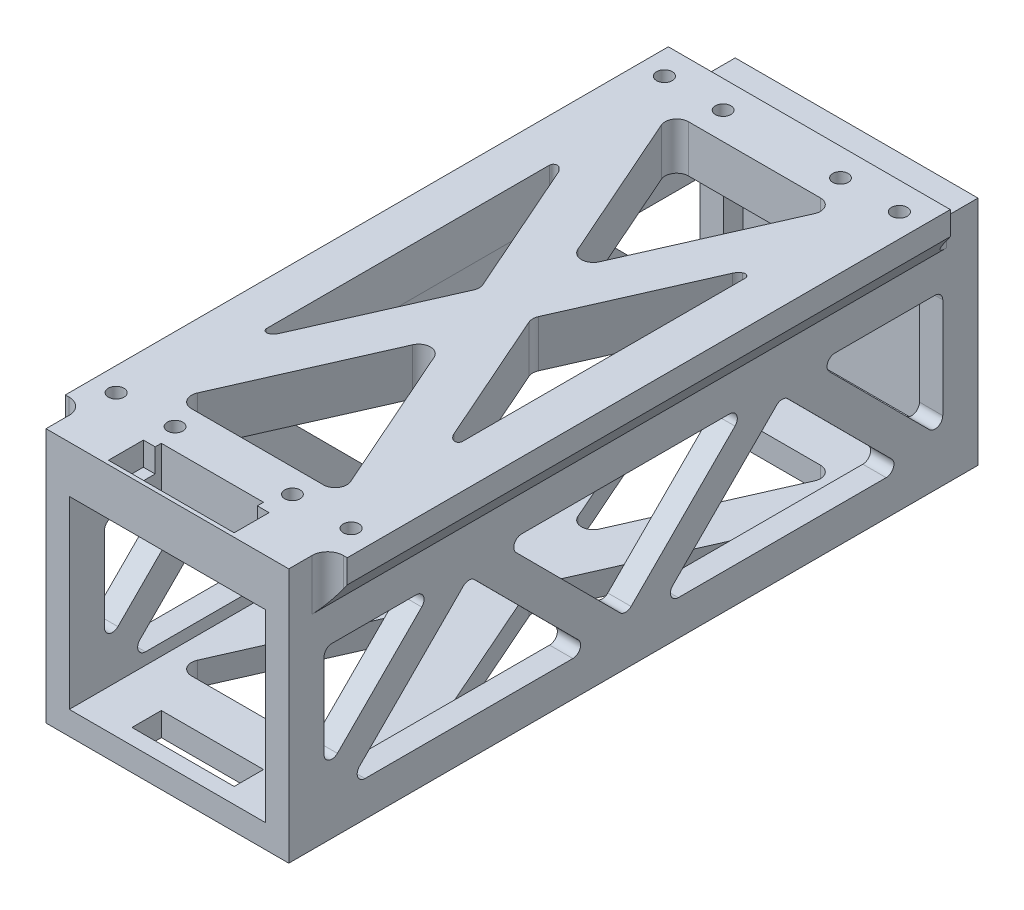
SolidWorks part; units mm, degrees
material "PBT General Purpose"
ref_plane "Front Plane" through (0, 0, 0) normal (0, 0, 1) x (1, 0, 0)
ref_plane "Top Plane" through (0, 0, 0) normal (0, 1, 0) x (1, 0, 0)
ref_plane "Right Plane" through (0, 0, 0) normal (1, 0, 0) x (0, 0, -1)
sketch "Sketch1" plane through (0, 0, 0) normal (0, 1, 0) x (1, 0, 0)
  line L1 (-31, -86) -> (31, -86)
  line L2 (-31, -86) -> (-31, 86)
  line L3 (-31, 86) -> (31, 86)
  line L4 (31, -86) -> (31, 86)
  line L5 (-31, -86) -> (31, 86) construction
  line L6 (-31, 86) -> (31, -86) construction
  point P0 (0, 0)
  dimension "D1" = 62
  dimension "D2" = 172
extrude "Boss-Extrude1" add sketch "Sketch1" along normal blind 6
sketch "Sketch2" plane through (0, 6, 0) normal (0, 1, 0) x (1, 0, 0)
  line L0 (-25.05, 86) -> (-31, 86)
  line L1 (25.05, -86) -> (31, -86)
  line L8 (25.05, -80.05) -> (25.05, 80.05)
  line L9 (25.05, 80.05) -> (-25.05, 80.05)
  line L10 (-25.05, 80.05) -> (-25.05, -80.05)
  line L11 (-25.05, -80.05) -> (25.05, -80.05)
  line L12 (25.05, -86) -> (25.05, 86)
  line L14 (-25.05, 86) -> (-25.05, -86)
  line L26 (-31, -86) -> (31, -86)
  line L27 (31, -86) -> (31, 86)
  line L28 (31, 86) -> (-31, 86)
  line L29 (-31, 86) -> (-31, -86)
  line L30 (-31, -86) -> (-25.05, -86)
  line L31 (31, -86) -> (31, 86)
  line L32 (31, 86) -> (25.05, 86)
  line L33 (-31, 86) -> (-31, -86)
  dimension "D3" = 5.95
  dimension "D1" = 5.95
  dimension "D2" = 0
extrude "Boss-Extrude2" add sketch "Sketch2" along normal blind 47.1
sketch "Sketch3" plane through (0, 53.1, 0) normal (0, 1, 0) x (1, 0, 0)
  line L1 (-31, 86) -> (31, 86)
  line L2 (-31, 86) -> (-31, -86)
  line L3 (-31, -86) -> (31, -86)
  line L4 (31, 86) -> (31, -86)
extrude "Boss-Extrude3" add sketch "Sketch3" along normal blind 6
sketch "Sketch4" plane through (0, 59.1, 0) normal (0, 1, 0) x (1, 0, 0)
  line L0 (-36, -76.0783) -> (36, -76.0783)
  line L1 (-36, -76.0783) -> (-36, 77.9217)
  line L2 (-36, 77.9217) -> (36, 77.9217)
  line L3 (36, -76.0783) -> (36, 77.9217)
  line L4 (-36, -76.0783) -> (36, 77.9217) construction
  line L5 (-36, 77.9217) -> (36, -76.0783) construction
  circle A0 centre (-30, 70.9217) radius 2
  circle A1 centre (-14.9851, 70.9012) radius 1.9746
  circle A2 centre (14.9851, 70.9012) radius 1.9746
  circle A3 centre (30, 70.9217) radius 2
  circle A4 centre (30, -69.0783) radius 2
  circle A5 centre (14.9851, -69.0578) radius 1.9746
  circle A6 centre (-14.9851, -69.0578) radius 1.9746
  circle A7 centre (-30, -69.0783) radius 2
  point P0 (0, 0.9217)
  dimension "D1" = 154
  dimension "D2" = 72
extrude "Boss-Extrude4" add sketch "Sketch4" along normal blind 6
sketch "Sketch5" plane through (0, 0, 0) normal (0, 0, 1) x (1, 0, 0)
  line L0 (-31, 59.1) -> (-31, 52.1)
  line L1 (-31, 59.1) -> (-31, 0) construction
  line L2 (-31, 59.1) -> (-36, 59.1)
  line L3 (-36, 59.1) -> (-31, 52.1)
  line L4 (0, 0) -> (0, 70.9697) construction
  line L5 (36, 59.1) -> (31, 52.1)
  line L6 (31, 59.1) -> (36, 59.1)
  line L7 (31, 59.1) -> (31, 52.1)
  dimension "D1" = 7
extrude "Boss-Extrude5" add sketch "Sketch5" along normal up to surface and the other way up to surface up to face at (0, 61.1, 76.0783) other way up to face at (0, 61.1, -77.9217)
fillet "Fillet2" radius 4 4 edges at (-31, 55.6, -77.9217) (31, 55.6, -77.9217) (-31, 55.6, 76.0783) (31, 55.6, 76.0783)
sketch "Sketch6" plane through (0, 0, -86) normal (0, 0, -1) x (-1, 0, 0)
  line L1 (-31, 59.1) -> (31, 59.1)
  line L2 (-31, 59.1) -> (-31, 0)
  line L3 (-31, 0) -> (31, 0)
  line L4 (31, 59.1) -> (31, 0)
extrude "Boss-Extrude6" add sketch "Sketch6" along normal blind 4
sketch "Sketch7" plane through (0, 59.1, 0) normal (0, 1, 0) x (1, 0, 0)
  line L0 (-31, -86) -> (31, -86) construction
  line L1 (-13.05, -74.5) -> (13.05, -74.5)
  line L2 (-13.05, -74.5) -> (-13.05, -82)
  line L3 (-13.05, -82) -> (13.05, -82)
  line L4 (13.05, -74.5) -> (13.05, -82)
  line L5 (-25.05, -86) -> (-25.05, 86) construction
  line L6 (25.05, 86) -> (25.05, -86) construction
  dimension "D1" = 7.5
  dimension "D2" = 4
  dimension "D3" = 12
  dimension "D4" = 12
extrude "Cut-Extrude1" cut sketch "Sketch7" against normal through all both and the other way through all
sketch "Sketch8" plane through (0, 59.1, 0) normal (0, 1, 0) x (1, 0, 0)
  line L16 (-13.05, -82) -> (-13.05, -76.0783)
  line L17 (-13.05, -76.0783) -> (-35, -76.0783)
  line L18 (-31, -80.0783) -> (-31, -86)
  line L19 (-31, -86) -> (31, -86)
  line L20 (31, -86) -> (31, -80.0783)
  line L21 (35, -76.0783) -> (13.05, -76.0783)
  line L22 (13.05, -76.0783) -> (13.05, -82)
  line L23 (13.05, -82) -> (-13.05, -82)
  line L25 (-16.05, -76.0783) -> (-35, -76.0783)
  line L26 (-31, -80.0783) -> (-31, -86)
  line L27 (-31, -86) -> (31, -86)
  line L28 (31, -86) -> (31, -80.0783)
  line L29 (35, -76.0783) -> (16.05, -76.0783)
  line L33 (16.05, -85) -> (16.05, -76.0783)
  line L34 (-16.05, -85) -> (16.05, -85)
  line L35 (-16.05, -76.0783) -> (-16.05, -85)
  line L36 (16.05, -85) -> (16.05, -76.0783)
  line L37 (-16.05, -85) -> (16.05, -85)
  line L38 (-16.05, -76.0783) -> (-16.05, -85)
  arc A4 (-31, -80.0783) -> (-35, -76.0783) centre (-35, -80.0783) ccw
  arc A5 (35, -76.0783) -> (31, -80.0783) centre (35, -80.0783) ccw
  arc A6 (-31, -80.0783) -> (-35, -76.0783) centre (-35, -80.0783) ccw
  arc A7 (35, -76.0783) -> (31, -80.0783) centre (35, -80.0783) ccw
  dimension "D1" = 0
  dimension "D2" = 3
extrude "Boss-Extrude7" add sketch "Sketch8" along normal up to surface (6 mm away) up to face at (0, 65.1, 37.1837)
sketch "Sketch9" plane through (31, 0, 0) normal (1, 0, 0) x (0, 0, -1)
  line L0 (52.0463, 39.6876) -> (77.584, 14.0859)
  line L5 (27.9537, 39.6876) -> (1.416, 13.0834)
  line L6 (-27.9537, 39.6876) -> (-1.416, 13.0834)
  line L8 (41.416, 39.0166) -> (67.9537, 12.4124)
  line L9 (38.584, 39.0166) -> (12.0463, 12.4124)
  line L10 (-38.584, 39.0166) -> (-12.0463, 12.4124)
  line L11 (-41.416, 39.0166) -> (-67.9537, 12.4124)
  line L12 (-77, 41.1) -> (-77, 19.5084)
  line L13 (-66.5378, 9) -> (-13.4622, 9)
  line L14 (81, 15.4984) -> (81, 41.1)
  line L15 (79, 43.1) -> (53.4622, 43.1)
  line L30 (13.4622, 9) -> (66.5378, 9)
  line L36 (-53.4622, 43.1) -> (-75, 43.1)
  line L39 (-52.0463, 39.6876) -> (-73.584, 18.0959)
  line L42 (26.5378, 43.1) -> (-26.5378, 43.1)
  arc A0 (53.4622, 43.1) -> (52.0463, 39.6876) centre (53.4622, 41.1) ccw
  arc A1 (81, 41.1) -> (79, 43.1) centre (79, 41.1) ccw
  arc A2 (81, 15.4984) -> (77.584, 14.0859) centre (79, 15.4984) cw
  arc A3 (67.9537, 12.4124) -> (66.5378, 9) centre (66.5378, 11) cw
  arc A4 (13.4622, 9) -> (12.0463, 12.4124) centre (13.4622, 11) cw
  arc A5 (41.416, 39.0166) -> (38.584, 39.0166) centre (40, 37.6041) ccw
  arc A6 (27.9537, 39.6876) -> (26.5378, 43.1) centre (26.5378, 41.1) ccw
  arc A7 (-27.9537, 39.6876) -> (-26.5378, 43.1) centre (-26.5378, 41.1) cw
  arc A8 (1.416, 13.0834) -> (-1.416, 13.0834) centre (0, 14.4959) cw
  arc A9 (-12.0463, 12.4124) -> (-13.4622, 9) centre (-13.4622, 11) cw
  arc A10 (-38.584, 39.0166) -> (-41.416, 39.0166) centre (-40, 37.6041) ccw
  arc A11 (-66.5378, 9) -> (-67.9537, 12.4124) centre (-66.5378, 11) cw
  arc A12 (-77, 19.5084) -> (-73.584, 18.0959) centre (-75, 19.5084) ccw
  arc A13 (-53.4622, 43.1) -> (-52.0463, 39.6876) centre (-53.4622, 41.1) cw
  arc A14 (-77, 41.1) -> (-75, 43.1) centre (-75, 41.1) cw
  dimension "D1" = 2
extrude "Cut-Extrude2" cut sketch "Sketch9" against normal through all both and the other way through all
sketch "Sketch11" plane through (0, 65.1, 0) normal (0, 1, 0) x (1, 0, 0)
  line L1 (-25, -35.6373) -> (-25, 36.559)
  line L2 (19.584, 59.7107) -> (2.7447, 21.5452)
  line L3 (22.2553, -35.1163) -> (7.0924, -0.7502)
  line L4 (22.2553, 36.038) -> (7.0924, 1.6719)
  line L5 (19.584, -58.789) -> (2.7447, -20.6235)
  line L6 (25, -35.6373) -> (25, 36.559)
  line L9 (-16.8393, -63) -> (16.8393, -63)
  line L10 (35, 63.9217) -> (-35, 63.9217)
  line L11 (16.8393, 63.9217) -> (-16.8393, 63.9217)
  line L14 (31, -86) -> (-31, -86) construction
  line L24 (-2.7447, -20.6235) -> (-19.584, -58.789)
  line L25 (-7.0924, 1.6719) -> (-22.2553, 36.038)
  line L26 (-2.7447, 21.5452) -> (-19.584, 59.7107)
  line L27 (-7.0924, -0.7502) -> (-22.2553, -35.1163)
  arc A0 (-22.2553, 36.038) -> (-23.5, 37.425) centre (-25, 34.827) ccw
  arc A1 (-23.5, -36.5033) -> (-22.2553, -35.1163) centre (-25, -33.9052) ccw
  arc A2 (-19.584, -58.789) -> (-16.8393, -63) centre (-16.8393, -60) ccw
  arc A3 (-7.0924, 1.6719) -> (-7.0924, -0.7502) centre (-9.8371, 0.4609) cw
  arc A4 (-23.5, 37.425) -> (-25, 36.559) centre (-24, 36.559) ccw
  arc A6 (-2.7447, -20.6235) -> (2.7447, -20.6235) centre (0, -21.8345) cw
  arc A7 (19.584, -58.789) -> (16.8393, -63) centre (16.8393, -60) cw
  arc A8 (23.5, -36.5033) -> (22.2553, -35.1163) centre (25, -33.9052) cw
  arc A9 (7.0924, 1.6719) -> (7.0924, -0.7502) centre (9.8371, 0.4609) ccw
  arc A10 (22.2553, 36.038) -> (23.5, 37.425) centre (25, 34.827) cw
  arc A11 (16.8393, 63.9217) -> (19.584, 59.7107) centre (16.8393, 60.9217) cw
  arc A12 (-16.8393, 63.9217) -> (-19.584, 59.7107) centre (-16.8393, 60.9217) ccw
  arc A13 (-2.7447, 21.5452) -> (2.7447, 21.5452) centre (0, 22.7562) ccw
  arc A14 (-25, -35.6373) -> (-23.5, -36.5033) centre (-24, -35.6373) ccw
  arc A15 (23.5, -36.5033) -> (25, -35.6373) centre (24, -35.6373) ccw
  arc A16 (25, 36.559) -> (23.5, 37.425) centre (24, 36.559) ccw
  point P24 (-6.5581, 0.4609)
  dimension "D4" = 3
  dimension "D1" = 1
  dimension "D3" = 23
  dimension "D2" = 14
extrude "Cut-Extrude3" cut sketch "Sketch11" against normal through all both and the other way through all
